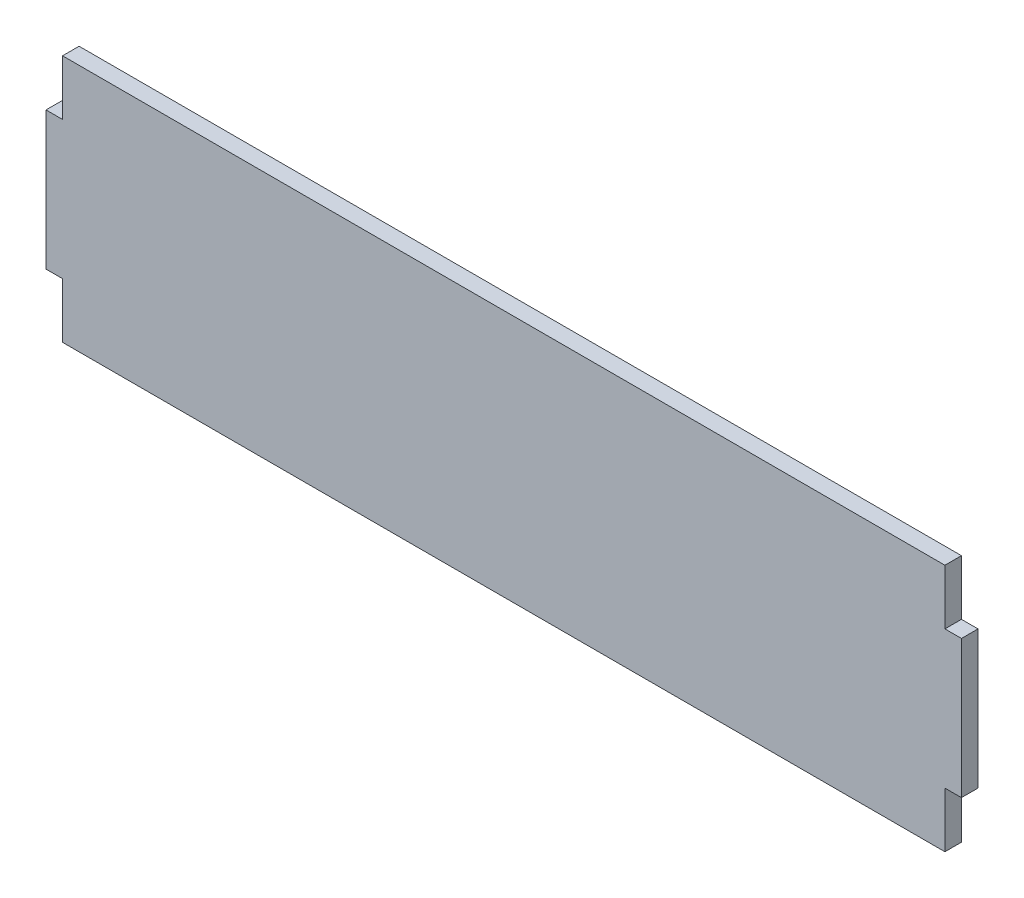
SolidWorks part; units mm, degrees
ref_plane "Front Plane" through (0, 0, 0) normal (0, 0, 1) x (1, 0, 0)
ref_plane "Top Plane" through (0, 0, 0) normal (0, 1, 0) x (1, 0, 0)
ref_plane "Right Plane" through (0, 0, 0) normal (1, 0, 0) x (0, 0, -1)
sketch "Sketch1" plane through (0, 0, 0) normal (0, 0, 1) x (1, 0, 0)
  line L0 (0, 17.8916) -> (142, 17.8916) construction
  line L1 (-160, 62.8916) -> (160, 62.8916)
  line L2 (-160, 62.8916) -> (-160, 42.8916)
  line L3 (-160, -27.1084) -> (160, -27.1084)
  line L4 (160, 62.8916) -> (160, 42.8916)
  line L5 (-160, 62.8916) -> (160, -27.1084) construction
  line L6 (-160, -27.1084) -> (160, 62.8916) construction
  line L7 (160, -7.1084) -> (160, -27.1084)
  line L8 (160, 42.8916) -> (166, 42.8916)
  line L10 (160, -7.1084) -> (166, -7.1084)
  line L11 (166, 42.8916) -> (166, -7.1084)
  line L12 (0, 17.8916) -> (0, -27.1084) construction
  line L13 (-160, -7.1084) -> (-166, -7.1084)
  line L14 (-166, 42.8916) -> (-166, -7.1084)
  line L15 (-160, 42.8916) -> (-166, 42.8916)
  line L16 (-160, -7.1084) -> (-160, -27.1084)
  point P0 (0, 17.8916)
  dimension "D1" = 320
  dimension "D2" = 90
  dimension "D3" = 6
  dimension "D4" = 50
extrude "Boss-Extrude1" add sketch "Sketch1" along normal blind 6
